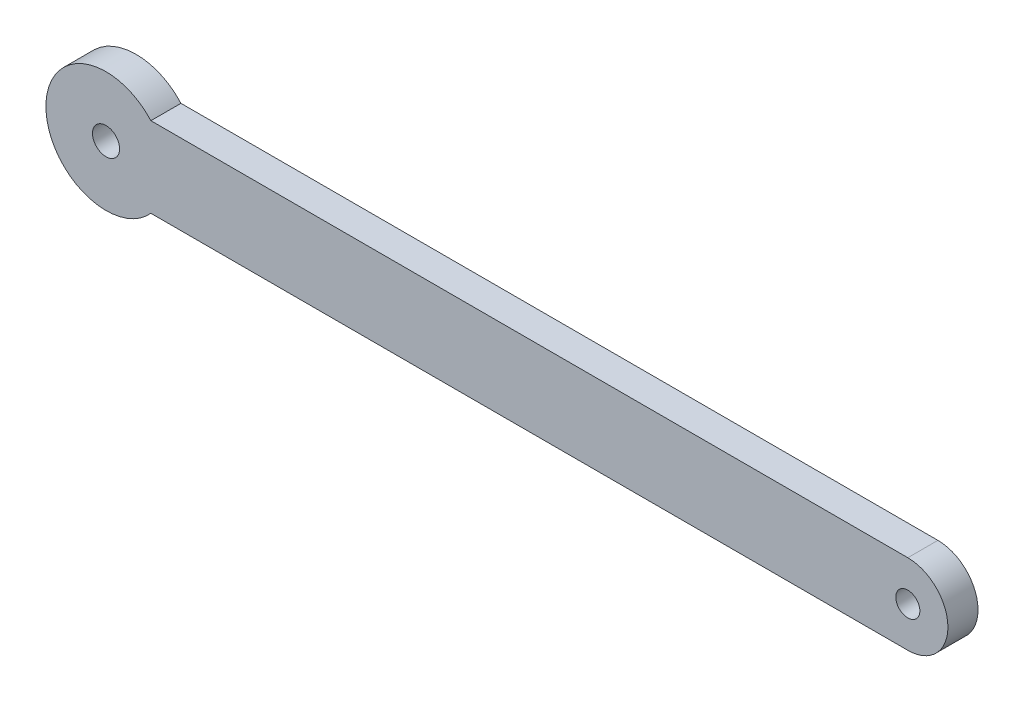
SolidWorks part; units mm, degrees
ref_plane "前视基准面" through (0, 0, 0) normal (0, 0, 1) x (1, 0, 0)
ref_plane "上视基准面" through (0, 0, 0) normal (0, 1, 0) x (1, 0, 0)
ref_plane "右视基准面" through (0, 0, 0) normal (1, 0, 0) x (0, 0, -1)
ref_plane "基准面1" through (0, 0, 0) normal (0, 0, -1) x (-1, 0, 0)
sketch "草图1" plane through (0, 0, 0) normal (0, 0, -1) x (-1, 0, 0)
  line L0 (51.4821, 7.5141) -> (-24.0193, 7.5141)
  line L1 (-24.0193, -0.4859) -> (51.4821, -0.4859)
  circle A0 centre (-24.0204, 3.5141) radius 1.2
  circle A1 centre (55.9543, 3.5141) radius 1.35
  arc A2 (-24.0193, 7.5141) -> (-24.0193, -0.4859) centre (-24.0193, 3.5141) ccw
  arc A3 (51.4821, -0.4859) -> (51.4821, 7.5141) centre (55.9543, 3.5141) ccw
extrude "凸台-拉伸1" add sketch "草图1" against normal blind 3
